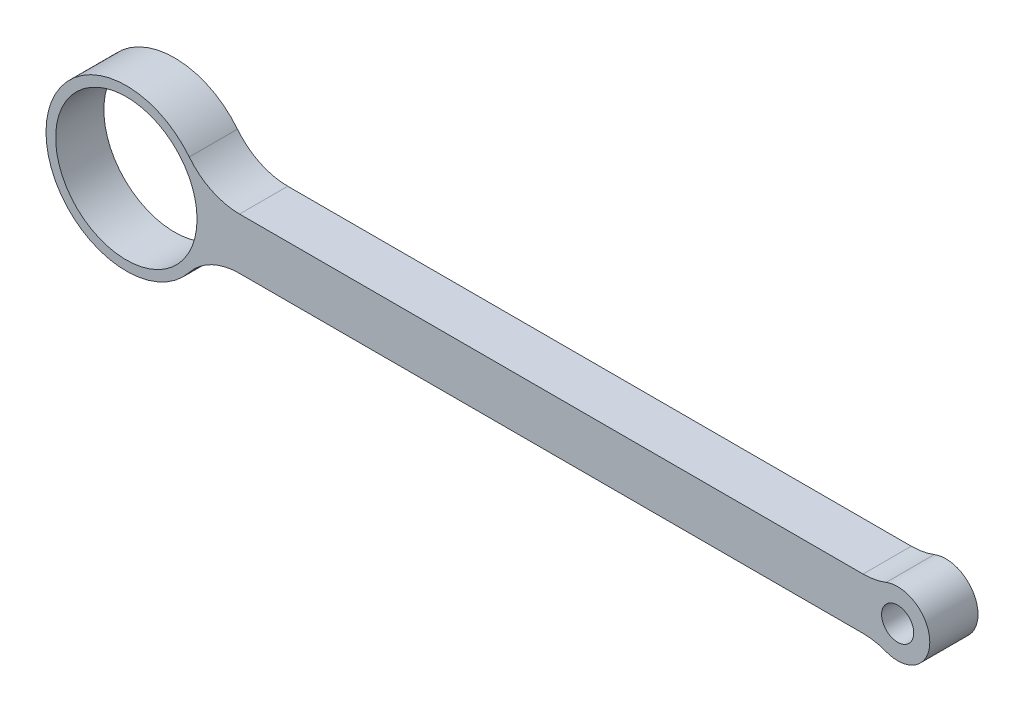
SolidWorks part; units mm, degrees
ref_plane "Front Plane" through (0, 0, 0) normal (0, 0, 1) x (1, 0, 0)
ref_plane "Top Plane" through (0, 0, 0) normal (0, 1, 0) x (1, 0, 0)
ref_plane "Right Plane" through (0, 0, 0) normal (1, 0, 0) x (0, 0, -1)
sketch "Sketch1" plane through (0, 0, 0) normal (0, 0, 1) x (1, 0, 0)
  line L0 (0, 0) -> (-60, 0) construction
  line L1 (-30, 0) -> (-30, 4) construction
  line L6 (0, 0) -> (0, 7.3353) construction
  line L11 (-62.5, -2.5) -> (-57.5, 2.5) construction
  line L12 (-62.5, 2.5) -> (-57.5, -2.5) construction
  line L13 (57, 4) -> (-48.1573, 4)
  line L15 (57, -4) -> (-48.1573, -4)
  circle A0 centre (0, 0) radius 2.5
  arc A12 (57, 4) -> (57, -4) centre (60, 0) cw
  circle A14 centre (60, 0) radius 2.5
  arc A15 (-48.1573, 4) -> (-48.1573, -4) centre (-60, 0) ccw
  circle A16 centre (-60, 0) radius 11
  dimension "D1" = 5
  dimension "D2" = 25
  dimension "D3" = 60
  dimension "D4" = 5
  dimension "D5" = 22
  dimension "D6" = 4
  dimension "D7" = 5
  dimension "D8" = 5
extrude "Boss-Extrude1" add sketch "Sketch1" along normal blind 7.5
fillet "Fillet1" radius 10 4 edges at (57, 4, 3.75) (57, -4, 3.75) (-48.1573, -4, 3.75) (-48.1573, 4, 3.75)
